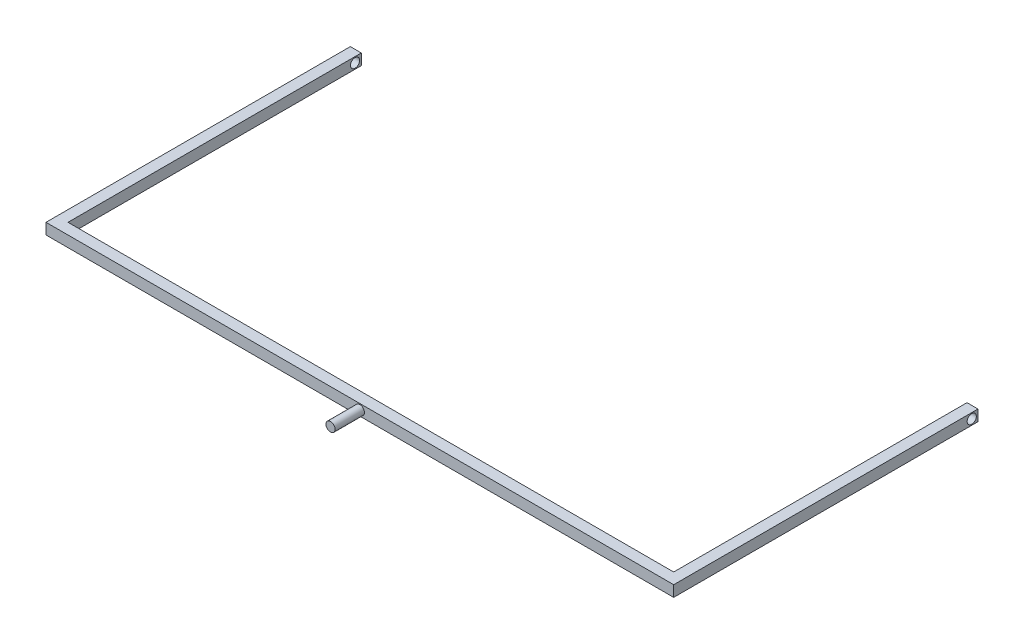
SolidWorks part; units mm, degrees
material "Простая углеродистая сталь"
ref_plane "Спереди" through (0, 0, 0) normal (0, 0, 1) x (1, 0, 0)
ref_plane "Сверху" through (0, 0, 0) normal (0, 1, 0) x (1, 0, 0)
ref_plane "Справа" through (0, 0, 0) normal (1, 0, 0) x (0, 0, -1)
other "Центр тяжести"
other "Configuration Table"
sketch "Эскиз1" plane through (0, 0, 0) normal (0, 1, 0) x (1, 0, 0)
  line L0 (1070, 0) -> (-642, 0)
  line L1 (-642, 0) -> (-642, 830)
  line L2 (-642, 830) -> (-612, 830)
  line L3 (-612, 830) -> (-612, 30)
  line L4 (-612, 30) -> (1040, 30)
  line L7 (1040, 830) -> (1040, 30)
  line L8 (1070, 830) -> (1040, 830)
  line L9 (1070, 0) -> (1070, 830)
  dimension "D1" = 30
  dimension "D2" = 30
  dimension "D3" = 30
  dimension "D4" = 1652
  dimension "D5" = 800
  dimension "D6" = 800
extrude "Бобышка-Вытянуть1" add sketch "Эскиз1" along normal blind 30
sketch "Эскиз3" plane through (-642, 0, 0) normal (-1, 0, 0) x (0, 0, 1)
  line L0 (-830, 30) -> (-830, 0) construction
  line L1 (-830, 30) -> (0, 30) construction
  circle A0 centre (-813, 15) radius 12.5
  dimension "D1" = 17
  dimension "D2" = 15
extrude "Вырез-Вытянуть1" cut sketch "Эскиз3" against normal through all
sketch "Эскиз5" plane through (0, 0, 0) normal (0, 0, 1) x (1, 0, 0)
  line L1 (-642, 30) -> (1070, 30) construction
  line L2 (-642, 30) -> (-642, 0) construction
  circle A0 centre (214, 15) radius 12.5
  dimension "D2" = 856
  dimension "D1" = 15
extrude "Вырез-Вытянуть2" cut sketch "Эскиз5" against normal through all
sketch "Эскиз7" plane through (0, 0, -30) normal (0, 0, -1) x (-1, 0, 0)
  circle A0 centre (-214, 15) radius 12.5
extrude "Бобышка-Вытянуть3" add sketch "Эскиз7" against normal blind 110
ref_point "Точка4"
